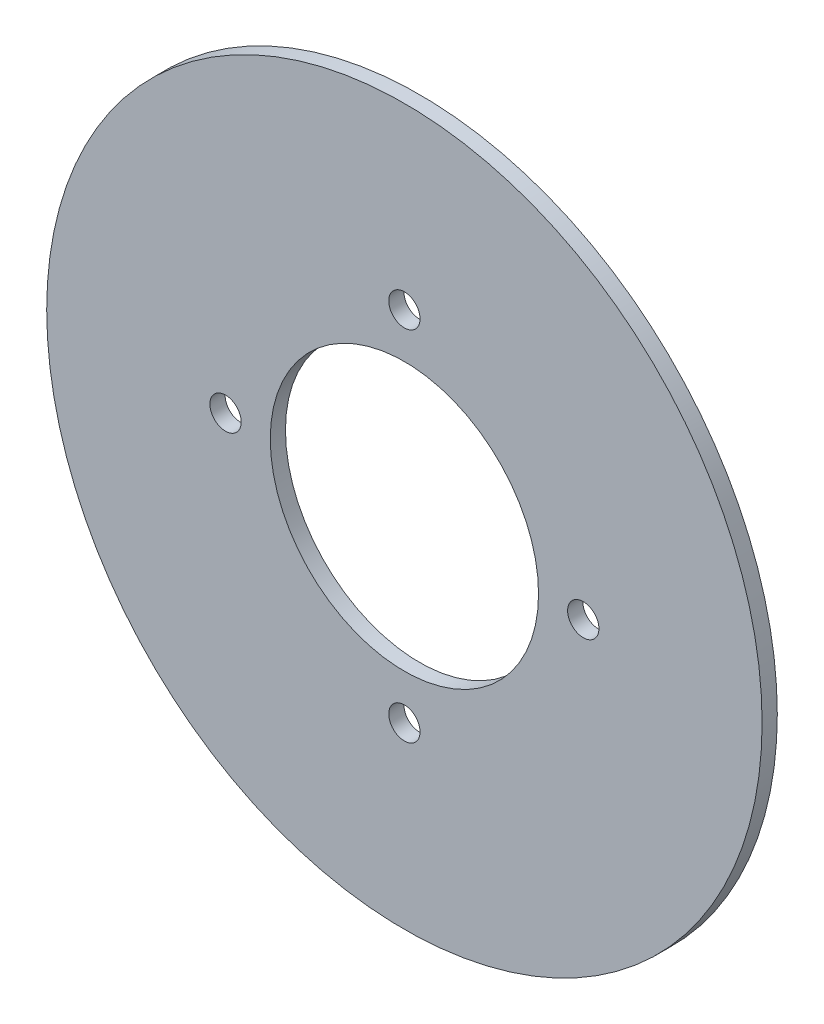
SolidWorks part; units mm, degrees
ref_plane "Front" through (0, 0, 0) normal (0, 0, 1) x (1, 0, 0)
ref_plane "Top" through (0, 0, 0) normal (0, 1, 0) x (1, 0, 0)
ref_plane "Right" through (0, 0, 0) normal (1, 0, 0) x (0, 0, -1)
sketch "Sketch1" plane through (0, 0, 0) normal (0, 0, 1) x (1, 0, 0)
  circle A0 centre (0, 0) radius 40
  circle A1 centre (0, 0) radius 15
  circle A2 centre (0, 20) radius 1.75
  circle A3 centre (20, 0) radius 1.75
  circle A4 centre (0, -20) radius 1.75
  circle A5 centre (-20, 0) radius 1.75
  point P15 (0, 0)
  dimension "D1" = 80
  dimension "D2" = 30
  dimension "D4" = 3.5
  dimension "D3" = 20
  dimension "D5" = 4
extrude "Boss-Extrude1" add sketch "Sketch1" along normal blind 1.7
